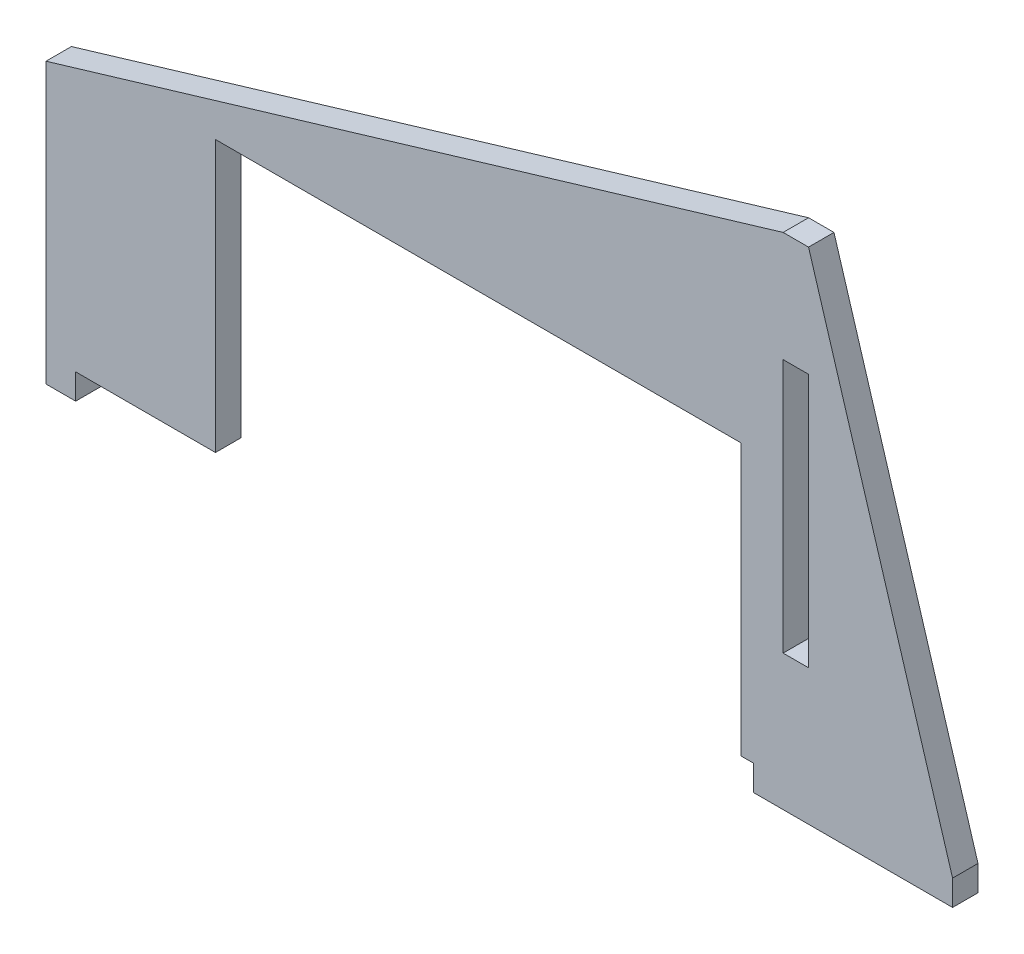
SolidWorks part; units mm, degrees
ref_plane "Front Plane" through (0, 0, 0) normal (0, 0, 1) x (1, 0, 0)
ref_plane "Top Plane" through (0, 0, 0) normal (0, 1, 0) x (1, 0, 0)
ref_plane "Right Plane" through (0, 0, 0) normal (1, 0, 0) x (0, 0, -1)
sketch "Sketch1" plane through (0, 0, 0) normal (0, 0, 1) x (1, 0, 0)
  line L0 (-90, 0) -> (-86.5, 0)
  line L1 (17, 0) -> (17, 3)
  line L2 (17, 3) -> (0, 59)
  line L3 (0, 59) -> (-3, 59)
  line L4 (-3, 59) -> (-90, 33)
  line L5 (-90, 33) -> (-90, 0)
  line L7 (-6.5, 0) -> (-6.5, 3) construction
  line L14 (-3, 46) -> (-3, 16)
  line L15 (-3, 16) -> (0, 16)
  line L16 (0, 16) -> (0, 46)
  line L17 (0, 46) -> (-3, 46)
  line L24 (-66.5, 3) -> (-86.5, 3) construction
  line L25 (-86.5, 3) -> (-86.5, 0) construction
  line L27 (-6.5, 0) -> (-6.5, 3)
  line L28 (-6.5, 3) -> (-8, 3)
  line L36 (-70, 3) -> (-86.5, 3)
  line L37 (-86.5, 3) -> (-86.5, 0)
  line L40 (-6.5, 0) -> (17, 0)
  line L42 (0, 59) -> (0, 0) construction
  line L45 (-70, 3) -> (-70, 35)
  line L46 (-70, 35) -> (-8, 35)
  line L47 (-8, 3) -> (-8, 35)
  dimension "D1" = 107
  dimension "D2" = 59
  dimension "D3" = 17
  dimension "D4" = 33
  dimension "D5" = 3
  dimension "D7" = 32
  dimension "D8" = 25
  dimension "D9" = 62
extrude "Boss-Extrude1" add sketch "Sketch1" along normal blind 3
